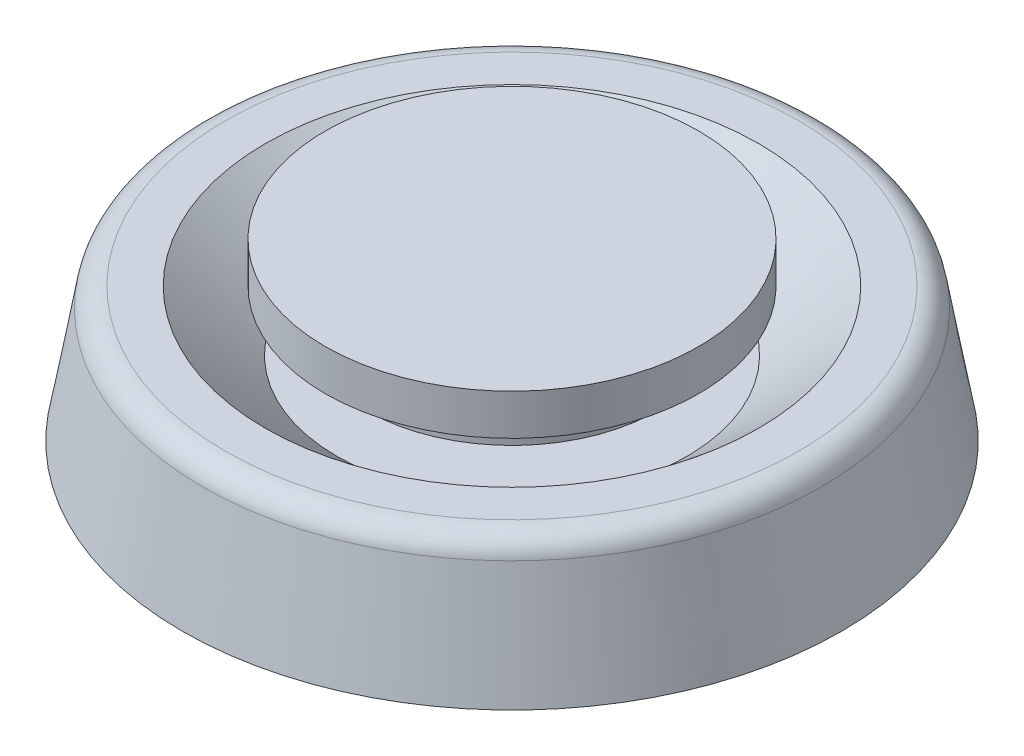
SolidWorks part; units mm, degrees
ref_plane "Front Plane" through (0, 0, 0) normal (0, 0, 1) x (1, 0, 0)
ref_plane "Top Plane" through (0, 0, 0) normal (0, 1, 0) x (1, 0, 0)
ref_plane "Right Plane" through (0, 0, 0) normal (1, 0, 0) x (0, 0, -1)
sketch "Sketch1" plane through (0, 0, 0) normal (0, 0, 1) x (1, 0, 0)
  line L0 (0, 0) -> (0, -25859.5842) construction
  line L1 (0, 0) -> (25859.5842, 0) construction
  line L2 (0, 0) -> (0, 15)
  line L3 (0, 15) -> (-16, 15)
  line L4 (-16, 15) -> (-16, 11.5)
  line L5 (-16, 11.5) -> (-12.5, 11.5)
  line L6 (-12.5, 11.5) -> (-12.5, 8.5)
  line L7 (-12.5, 8.5) -> (-7.5, 8.5)
  line L8 (-7.5, 8.5) -> (-7.5, 6.3548)
  line L9 (-7.5, 6.3548) -> (-15, 6.3548)
  line L10 (-15, 6.3548) -> (-21.1318, 11.5)
  line L11 (-21.1318, 11.5) -> (-24.544, 11.5)
  line L12 (-26.5137, 9.8473) -> (-28.25, 0)
  line L13 (-28.25, 0) -> (0, 0)
  arc A0 (-24.544, 11.5) -> (-26.5137, 9.8473) centre (-24.544, 9.5) ccw
  dimension "D12" = 2
  dimension "D1" = 3.5
  dimension "D2" = 3.5
  dimension "D3" = 5
  dimension "D4" = 3
  dimension "D5" = 7.5
  dimension "D6" = 40
  dimension "D7" = 0
  dimension "D8" = 32
  dimension "D9" = 11.5
  dimension "D10" = 56.5
  dimension "D11" = 100
revolve "Revolve1" add sketch "Sketch1" angle 360 about L0
